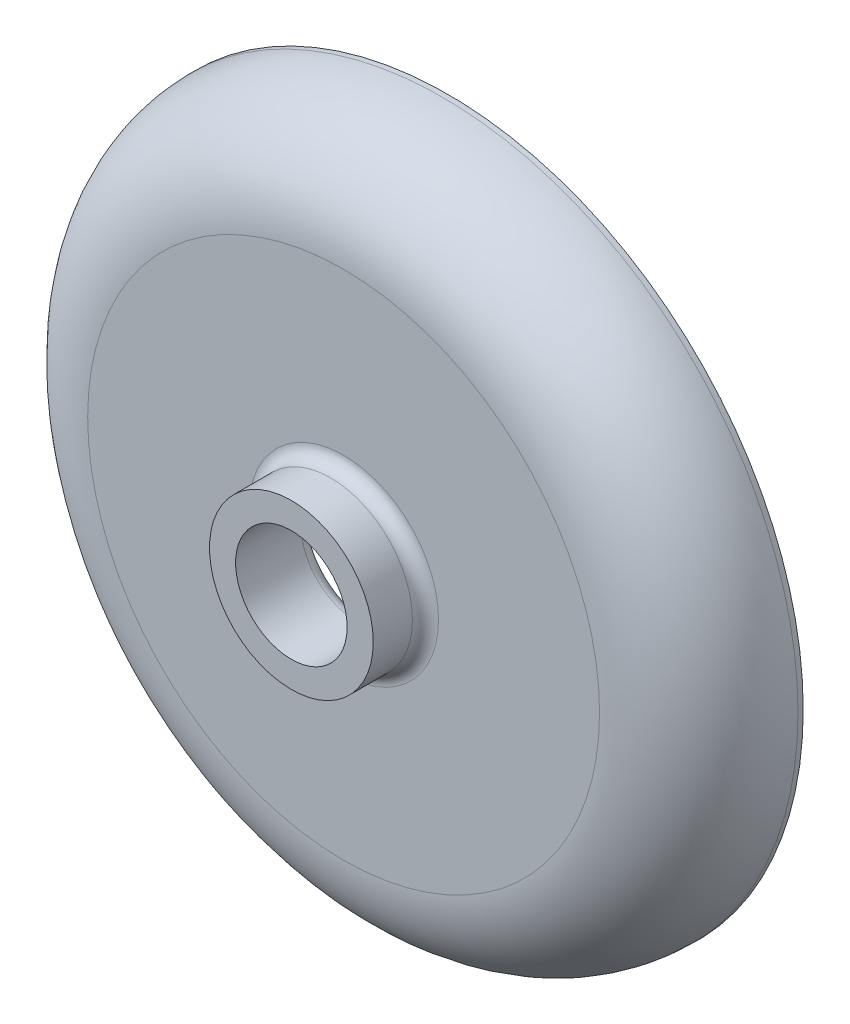
SolidWorks part; units mm, degrees
ref_plane "Plane1" through (0, 0, 0) normal (0, 0, 1) x (1, 0, 0)
ref_plane "Plane2" through (0, 0, 0) normal (0, 1, 0) x (1, 0, 0)
ref_plane "Plane3" through (0, 0, 0) normal (1, 0, 0) x (0, 0, -1)
other "Configuration Table"
sketch "Sketch1" plane through (0, 0, 0) normal (0, 0, 1) x (1, 0, 0)
  circle A0 centre (0, 0) radius 13.6
  dimension "D1" = 27.2
extrude "drive shaft plate shape" add sketch "Sketch1" along normal blind 4
fillet "plate main fillet" radius 3.8 1 edges at (13.6, 0, 4)
sketch "Sketch2" plane through (0, 0, 4) normal (0, 0, 1) x (1, 0, 0)
  circle A0 centre (0, 0) radius 3.135
  dimension "D1" = 6.27
extrude "plate boss" add sketch "Sketch2" along normal blind 2
shell "plate shell" thickness 1
sketch "Sketch3" plane through (0, 0, 6) normal (0, 0, 1) x (1, 0, 0)
  circle A0 centre (0, 0) radius 2.135
  dimension "D1" = 4.27
extrude "drive plate hole" cut sketch "Sketch3" against normal up to next
fillet "drive plate secondary fillet" radius 0.5 2 edges at (2.135, 0, 3) (3.135, 0, 4)
